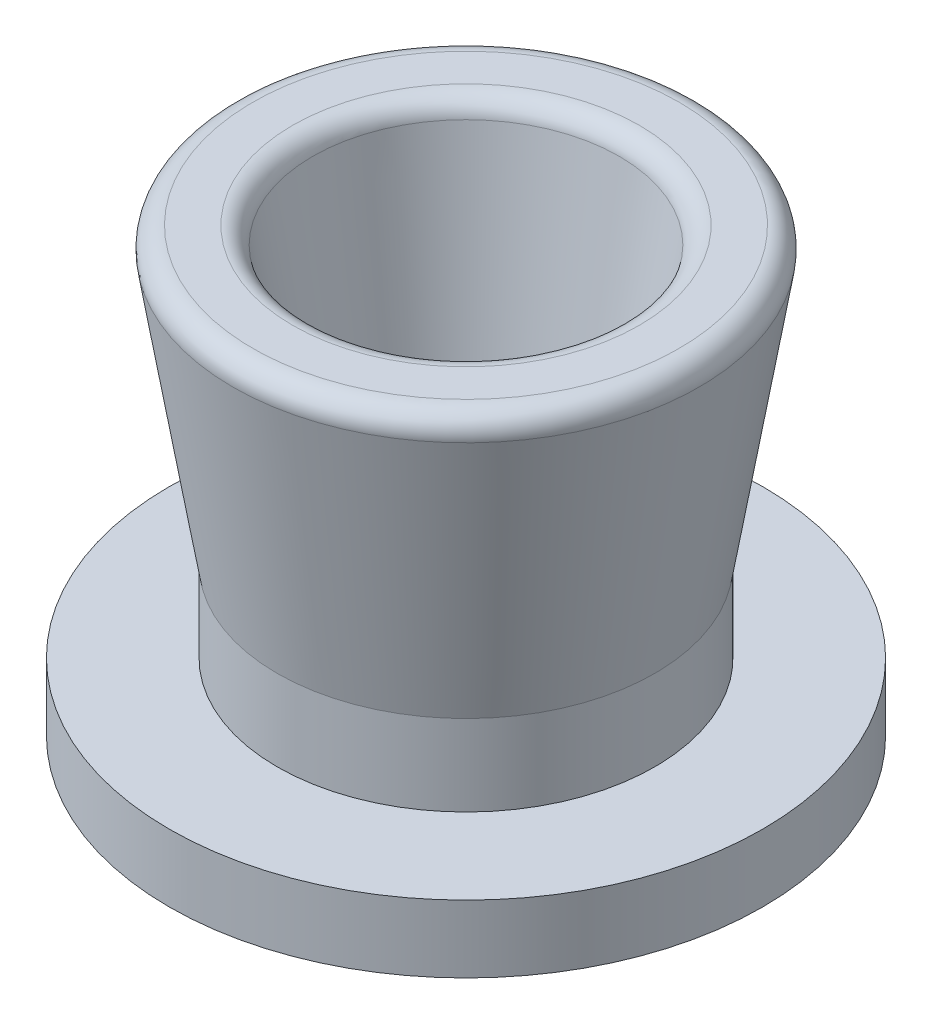
SolidWorks part; units mm, degrees
ref_plane "Front Plane" through (0, 0, 0) normal (0, 0, 1) x (1, 0, 0)
ref_plane "Top Plane" through (0, 0, 0) normal (0, 1, 0) x (1, 0, 0)
ref_plane "Right Plane" through (0, 0, 0) normal (1, 0, 0) x (0, 0, -1)
sketch "Sketch1" plane through (0, 0, 0) normal (0, 1, 0) x (1, 0, 0)
  circle A0 centre (0, 0) radius 8
  circle A1 centre (0, 0) radius 22
extrude "Boss-Extrude1" add sketch "Sketch1" along normal blind 5
sketch "Sketch2" plane through (0, 5, 0) normal (0, 1, 0) x (1, 0, 0)
  circle A0 centre (0, 0) radius 8
  circle A1 centre (0, 0) radius 14
extrude "Boss-Extrude2" add sketch "Sketch2" along normal blind 6
sketch "Sketch3" plane through (0, 0, 0) normal (0, 0, 1) x (1, 0, 0)
  line L0 (8, 11) -> (11.3703, 31.5194)
  line L1 (12.8505, 32.7763) -> (15.8103, 32.7763)
  line L2 (17.2905, 31.0332) -> (14, 11)
  line L3 (8, 11) -> (14, 11)
  line L4 (0, 0) -> (0, 26.8398) construction
  arc A0 (12.8505, 32.7763) -> (11.3703, 31.5194) centre (12.8505, 31.2763) ccw
  arc A1 (17.2905, 31.0332) -> (15.8103, 32.7763) centre (15.8103, 31.2763) ccw
  dimension "D1" = 1.5
revolve "Revolve1" add sketch "Sketch3" angle 360 about L4
